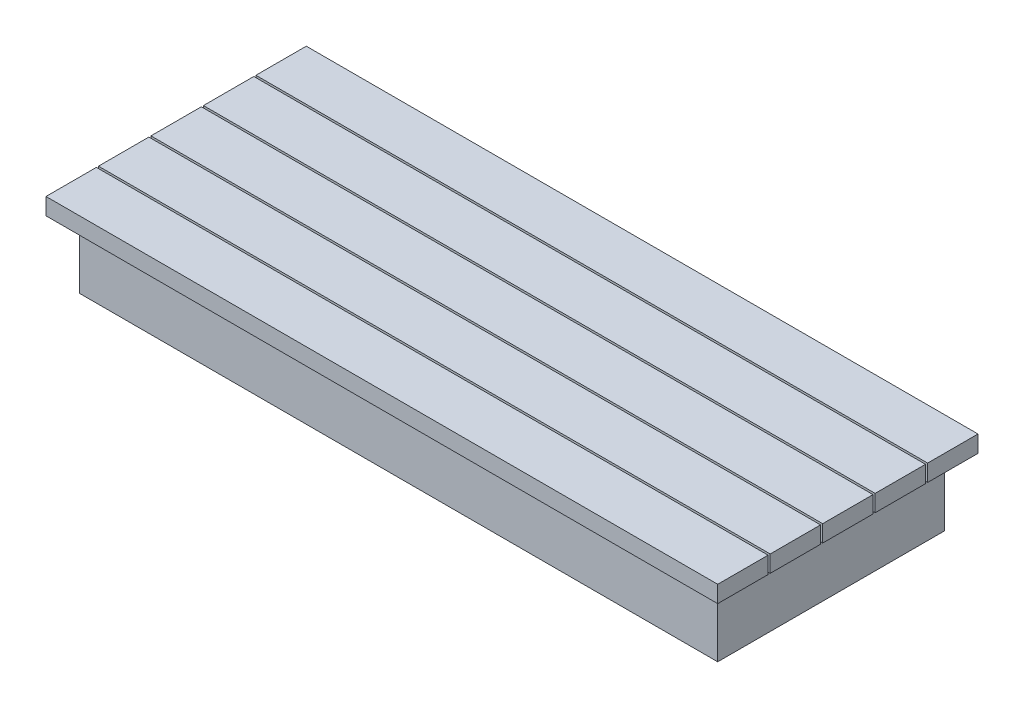
SolidWorks part; units mm, degrees
ref_plane "Front Plane" through (0, 0, 0) normal (0, 0, 1) x (1, 0, 0)
ref_plane "Top Plane" through (0, 0, 0) normal (0, 1, 0) x (1, 0, 0)
ref_plane "Right Plane" through (0, 0, 0) normal (1, 0, 0) x (0, 0, -1)
sketch "Sketch1" plane through (0, 0, 0) normal (0, 1, 0) x (1, 0, 0)
  line L7 (1016, 76.2) -> (-1016, 76.2)
  line L8 (-1016, 76.2) -> (-1016, -76.2)
  line L9 (-1016, -76.2) -> (1016, -76.2)
  line L20 (1016, 76.2) -> (1016, -76.2)
  line L21 (1016, 234.95) -> (-1016, 234.95)
  line L22 (-1016, 234.95) -> (-1016, 82.55)
  line L23 (-1016, 82.55) -> (1016, 82.55)
  line L24 (1016, 234.95) -> (1016, 82.55)
  line L25 (1016, 393.7) -> (-1016, 393.7)
  line L26 (-1016, 393.7) -> (-1016, 241.3)
  line L27 (-1016, 241.3) -> (1016, 241.3)
  line L28 (1016, 393.7) -> (1016, 241.3)
  line L29 (1016, -82.55) -> (-1016, -82.55)
  line L30 (-1016, -82.55) -> (-1016, -234.95)
  line L31 (-1016, -234.95) -> (1016, -234.95)
  line L32 (1016, -82.55) -> (1016, -234.95)
  line L33 (1016, -241.3) -> (-1016, -241.3)
  line L34 (-1016, -241.3) -> (-1016, -393.7)
  line L35 (-1016, -393.7) -> (1016, -393.7)
  line L36 (1016, -241.3) -> (1016, -393.7)
  dimension "D1" = 3
  dimension "D2" = 3
extrude "Boss-Extrude1" add sketch "Sketch1" along normal blind 50.8
sketch "Sketch2" plane through (0, 0, 0) normal (0, -1, 0) x (-1, 0, 0)
  line L13 (965.2, -342.9) -> (-965.2, -342.9)
  line L14 (965.2, -342.9) -> (965.2, 342.9)
  line L15 (965.2, 342.9) -> (-965.2, 342.9)
  line L16 (-965.2, -342.9) -> (-965.2, 342.9)
  line L17 (914.4, -292.1) -> (-914.4, -292.1)
  line L18 (914.4, -292.1) -> (914.4, 292.1)
  line L19 (914.4, 292.1) -> (-914.4, 292.1)
  line L20 (-914.4, -292.1) -> (-914.4, 292.1)
extrude "Boss-Extrude2" add sketch "Sketch2" along normal blind 203.2
